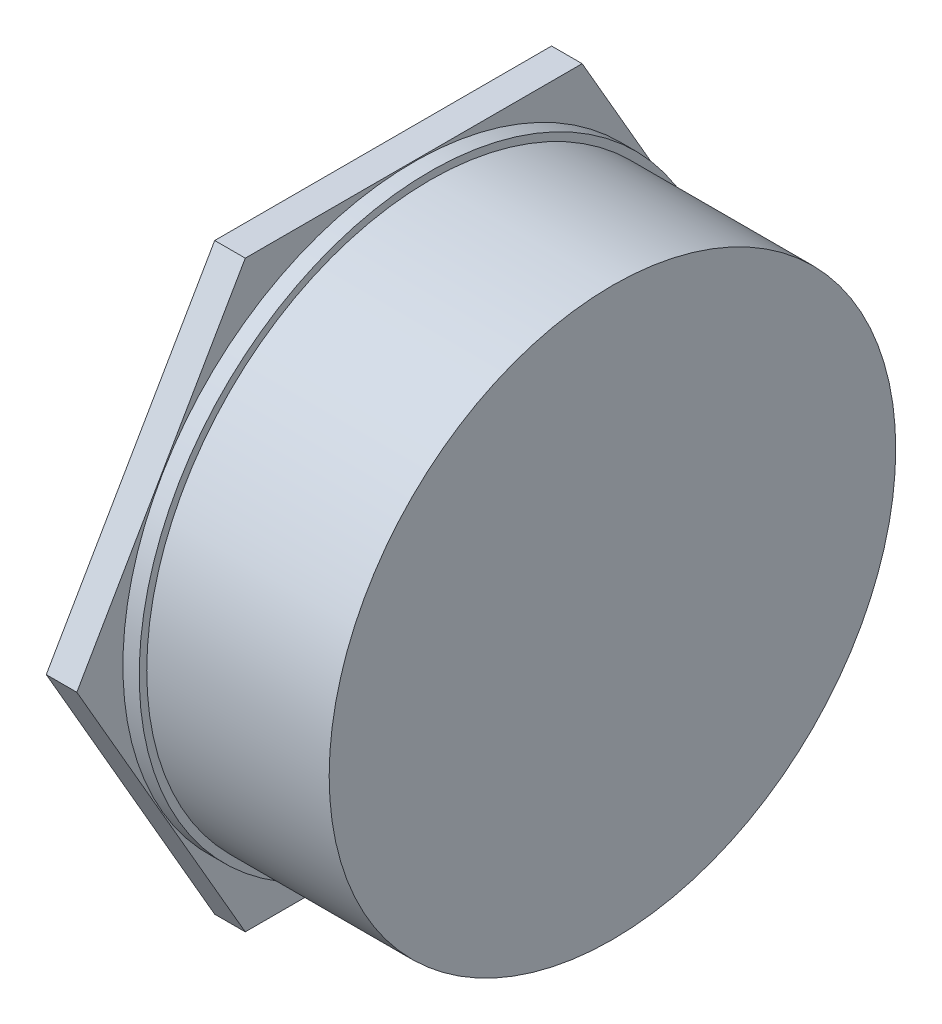
SolidWorks part; units mm, degrees
material "AISI 304"
ref_plane "Front" through (0, 0, 0) normal (0, 0, 1) x (1, 0, 0)
ref_plane "Top" through (0, 0, 0) normal (0, 1, 0) x (1, 0, 0)
ref_plane "Right" through (0, 0, 0) normal (1, 0, 0) x (0, 0, -1)
sketch "Sketch1" plane through (0, 0, 0) normal (1, 0, 0) x (0, 0, -1)
  line L1 (33.0533, 57.25) -> (-33.0533, 57.25)
  line L2 (-33.0533, 57.25) -> (-66.1066, 0)
  line L3 (-66.1066, 0) -> (-33.0533, -57.25)
  line L4 (-33.0533, -57.25) -> (33.0533, -57.25)
  line L5 (33.0533, -57.25) -> (66.1066, 0)
  line L6 (66.1066, 0) -> (33.0533, 57.25)
  circle A0 centre (0, 0) radius 57.25 construction
  dimension "D1" = 114.5
extrude "Boss-Extrude1" add sketch "Sketch1" along normal blind 6
sketch "Sketch2" plane through (6, 0, 0) normal (1, 0, 0) x (0, 0, -1)
  circle A0 centre (0, 0) radius 57.07
  dimension "D1" = 114.14
extrude "Boss-Extrude2" add sketch "Sketch2" along normal blind 39
sketch "Sketch3" plane through (45, 0, 0) normal (1, 0, 0) x (0, 0, -1)
  circle A0 centre (0, 0) radius 55.591
  circle A1 centre (0, 0) radius 57.07 construction
  circle A2 centre (0, 0) radius 57.07
  dimension "D1" = 1.479
extrude "Cut-Extrude1" cut sketch "Sketch3" against normal blind 35.8
